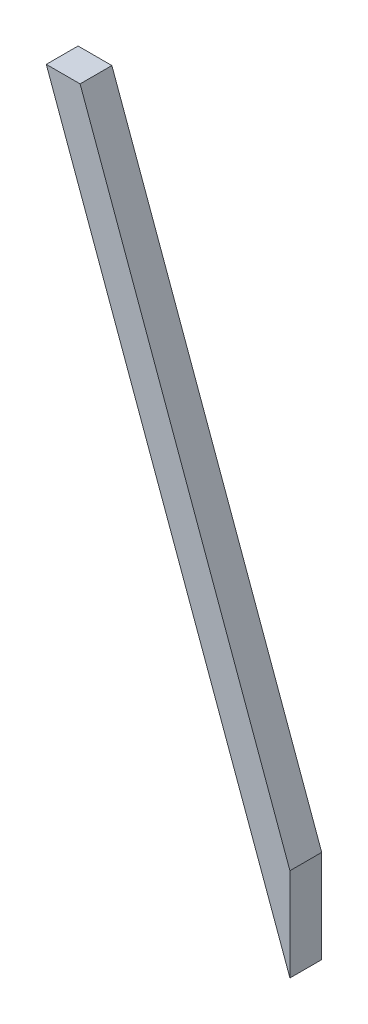
SolidWorks part; units mm, degrees
ref_plane "Front Plane" through (0, 0, 0) normal (1, 0, 0) x (0, 1, 0)
ref_plane "Top Plane" through (0, 0, 0) normal (0, 0, 1) x (0, 1, 0)
ref_plane "Right Plane" through (0, 0, 0) normal (0, 1, 0) x (-1, 0, 0)
sketch "Sketch1" plane through (0, 0, 0) normal (0, 0, 1) x (0, 1, 0)
  line L0 (-49.7447, 1.7991) -> (76.6628, 47.8077)
  line L1 (76.6628, 47.8077) -> (76.6628, 41.4226)
  line L2 (-32.2018, 1.7991) -> (-49.7447, 1.7991)
  line L3 (76.6628, 41.4226) -> (-32.2018, 1.7991)
  dimension "D1" = 134.52
  dimension "D2" = 20
  dimension "D3" = 6
extrude "Boss-Extrude1" add sketch "Sketch1" along normal blind 6
